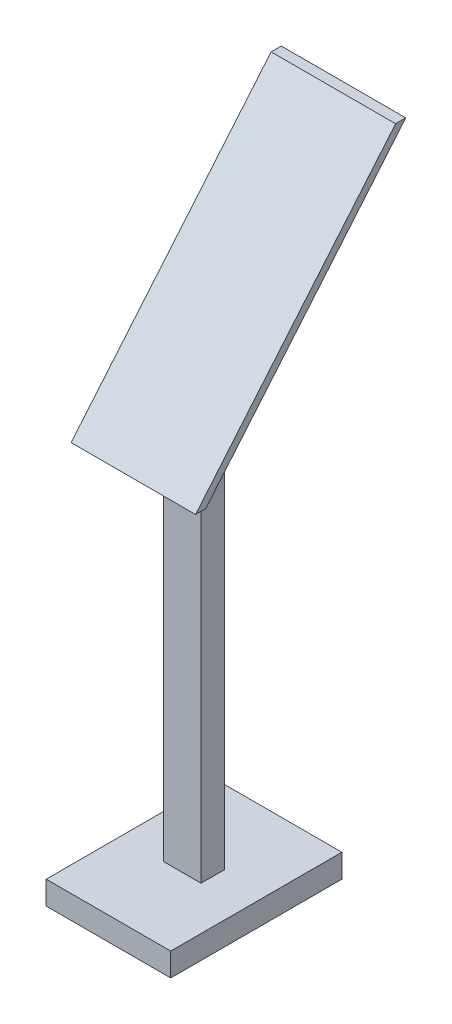
SolidWorks part; units mm, degrees
ref_plane "前视基准面" through (0, 0, 0) normal (0, 0, 1) x (1, 0, 0)
ref_plane "上视基准面" through (0, 0, 0) normal (0, 1, 0) x (1, 0, 0)
ref_plane "右视基准面" through (0, 0, 0) normal (1, 0, 0) x (0, 0, -1)
sketch "草图1" plane through (0, 0, 0) normal (1, 0, 0) x (0, 0, -1)
  line L0 (0, 0) -> (0, 49.9432) construction
  line L1 (55, 0) -> (-55, 0)
  line L2 (-55, 0) -> (-55, 15)
  line L3 (-55, 15) -> (-7.5, 15)
  line L4 (-7.5, 15) -> (-7.5, 279.7938)
  line L5 (55, 15) -> (7.5, 15)
  line L6 (55, 0) -> (55, 15)
  line L7 (7.5, 15) -> (7.5, 297.6701)
  line L8 (7.5, 297.6701) -> (96.0575, 403.2089)
  line L10 (89.5305, 403.2089) -> (-39.027, 250)
  line L12 (-32.5, 250) -> (-7.5, 279.7938)
  line L13 (-7.5, 15) -> (7.5, 15) construction
  line L14 (89.5305, 403.2089) -> (96.0575, 403.2089)
  line L15 (-39.027, 250) -> (-32.5, 250)
  point P2 (-8.0493, 32.1983)
  point P13 (193.6682, 250)
  point P16 (117.0097, 250)
  point P18 (0, 0)
  point P19 (186.7698, 403.2089)
  point P20 (-30.4363, 250)
  point P21 (-53.1048, 250)
  point P22 (-31.817, 10.4992)
  point P23 (-7.5, 280.495)
  point P24 (-50.6843, 15)
  dimension "D1" = 140
  dimension "D2" = 200
  dimension "D3" = 250
  dimension "D4" = 5
  dimension "D5" = 15
  dimension "D6" = 25
  dimension "D7" = 110
extrude "凸台-拉伸1" add sketch "草图1" along normal mid plane 80
sketch "草图2" plane through (40, 0, 0) normal (1, 0, 0) x (0, 0, -1)
  line L0 (-7.5, 279.7938) -> (7.5, 297.6701)
  line L1 (7.5, 297.6701) -> (7.5, 15)
  line L2 (7.5, 15) -> (-7.5, 15)
  line L3 (-7.5, 279.7938) -> (-7.5, 15) construction
  line L4 (-7.5, 279.7938) -> (-7.5, 15)
extrude "切除-拉伸1" cut sketch "草图2" against normal blind 28
mirror "镜向1" about plane through (0, 0, 0) normal (1, 0, 0) of "切除-拉伸1"
